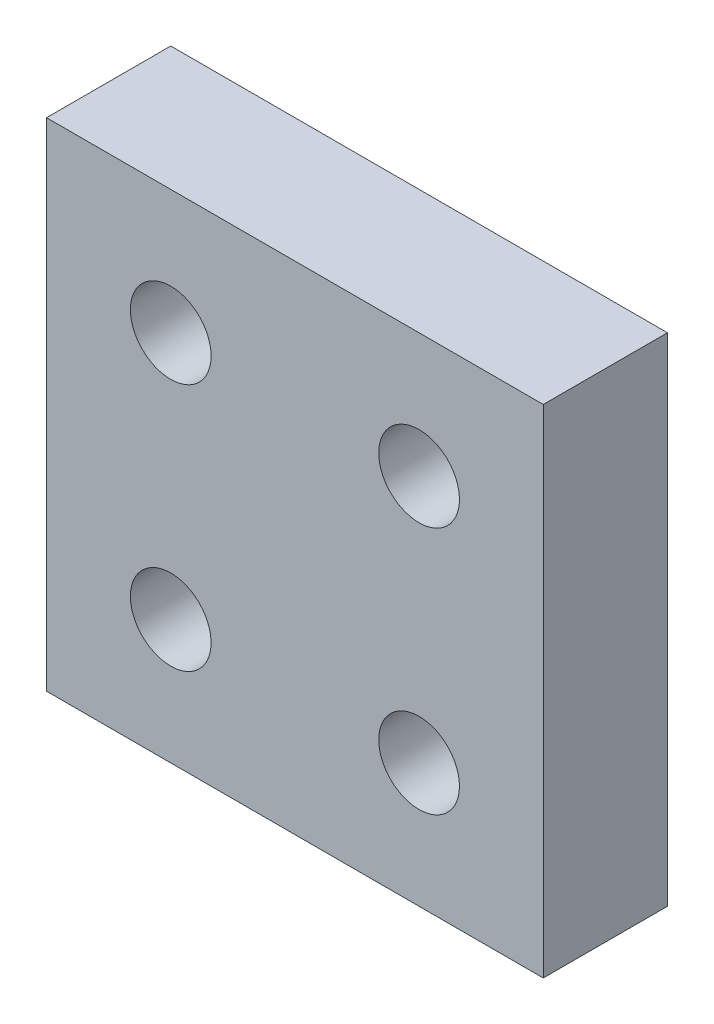
SolidWorks part; units mm, degrees
ref_plane "前视基准面" through (0, 0, 0) normal (0, 0, 1) x (1, 0, 0)
ref_plane "上视基准面" through (0, 0, 0) normal (0, 1, 0) x (1, 0, 0)
ref_plane "右视基准面" through (0, 0, 0) normal (1, 0, 0) x (0, 0, -1)
other "Configuration Table"
sketch "草图1" plane through (0, 0, 0) normal (0, 0, 1) x (1, 0, 0)
  line L1 (0, 0) -> (20, 0)
  line L2 (0, 0) -> (0, -20)
  line L3 (0, -20) -> (20, -20)
  line L4 (20, 0) -> (20, -20)
  dimension "D1" = 20
  dimension "D2" = 20
extrude "凸台-拉伸1" add sketch "草图1" along normal blind 5
sketch "草图2" plane through (0, 0, 5) normal (0, 0, 1) x (1, 0, 0)
  line L0 (20, -10) -> (0, -10) construction
  line L1 (20, -20) -> (20, 0) construction
  line L2 (0, 0) -> (0, -20) construction
  line L3 (10, 0) -> (10, -20) construction
  line L4 (20, 0) -> (0, 0) construction
  line L5 (0, -20) -> (20, -20) construction
  circle A0 centre (5, -5) radius 1.625
  circle A1 centre (15, -5) radius 1.625
  circle A2 centre (15, -15) radius 1.625
  circle A3 centre (5, -15) radius 1.625
  dimension "D3" = 3.25
  dimension "D1" = 5
  dimension "D2" = 5
extrude "切除-拉伸1" cut sketch "草图2" against normal through all
